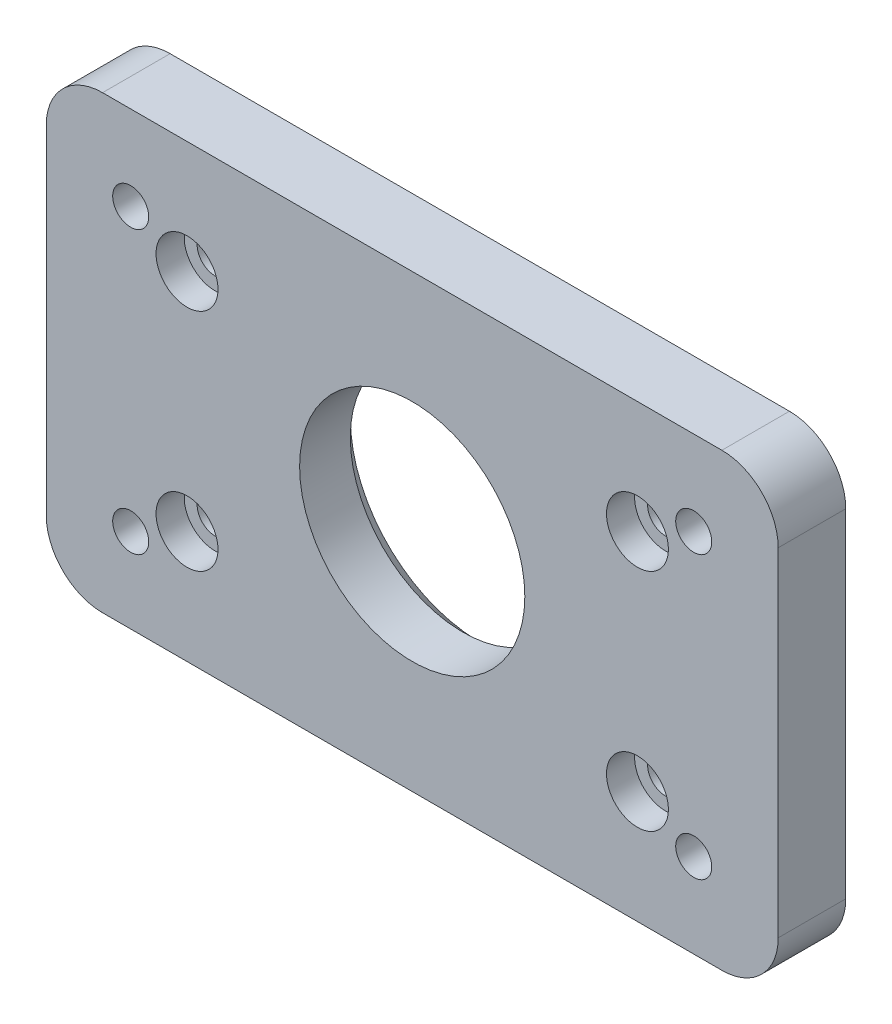
SolidWorks part; units mm, degrees
ref_plane "前视基准面" through (0, 0, 0) normal (0, 0, 1) x (1, 0, 0)
ref_plane "上视基准面" through (0, 0, 0) normal (0, 1, 0) x (1, 0, 0)
ref_plane "右视基准面" through (0, 0, 0) normal (1, 0, 0) x (0, 0, -1)
sketch "草图1" plane through (0, 0, 0) normal (0, 0, 1) x (1, 0, 0)
  line L5 (-50, 40) -> (50, 40)
  line L6 (-50, -40) -> (50, -40)
  line L7 (-50, -40) -> (-65, -40)
  line L8 (-65, -40) -> (-65, 40)
  line L9 (-65, 40) -> (-50, 40)
  line L10 (50, 40) -> (65, 40)
  line L11 (65, 40) -> (65, -40)
  line L12 (65, -40) -> (50, -40)
  circle A1 centre (50, 25) radius 3.2
  circle A3 centre (-50, 25) radius 3.2
  circle A4 centre (50, -25) radius 3.2
  circle A5 centre (-50, -25) radius 3.2
  circle A6 centre (0, 0) radius 20
  circle A15 centre (-40, 20) radius 3.2
  circle A16 centre (-40, -20) radius 3.2
  circle A17 centre (40, -20) radius 3.2
  circle A18 centre (40, 20) radius 3.2
  point P12 (-50, 0)
extrude "凸台-拉伸1" add sketch "草图1" along normal blind 12
fillet "圆角1" radius 10 4 edges at (65, 40, 6) (65, -40, 6) (-65, 40, 6) (-65, -40, 6)
chamfer "倒角1" distance 3 angle 45 1 edges at (20, 0, 0)
sketch "草图2" plane through (0, 0, 12) normal (0, 0, 1) x (1, 0, 0)
  circle A0 centre (-40, 20) radius 5.5
  circle A1 centre (-40, -20) radius 5.5
  circle A2 centre (40, 20) radius 5.5
  circle A3 centre (40, -20) radius 5.5
extrude "切除-拉伸1" cut sketch "草图2" against normal blind 5
